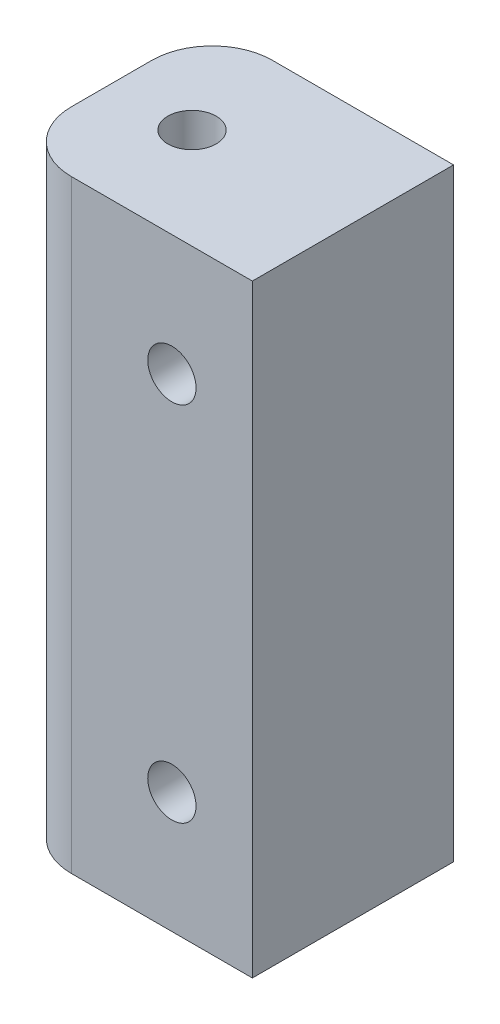
SolidWorks part; units mm, degrees
material "ABS"
ref_plane "Plan de face" through (0, 0, 0) normal (0, 0, 1) x (1, 0, 0)
ref_plane "Plan de dessus" through (0, 0, 0) normal (0, 1, 0) x (1, 0, 0)
ref_plane "Plan de droite" through (0, 0, 0) normal (1, 0, 0) x (0, 0, -1)
sketch "Esquisse1" plane through (0, 0, 0) normal (0, 1, 0) x (1, 0, 0)
  line L1 (-6, 10) -> (6, 10)
  line L2 (-6, 10) -> (-6, 0)
  line L3 (-6, 0) -> (6, 0)
  line L4 (6, 10) -> (6, 0)
  circle A0 centre (-2, 5) radius 1.2
  dimension "D3" = 2.4
  dimension "D4" = 4
  dimension "D5" = 5
  dimension "D1" = 12
  dimension "D2" = 10
extrude "Boss.-Extru.1" add sketch "Esquisse1" along normal mid plane 30
sketch "Esquisse2" plane through (0, 0, 0) normal (0, 0, 1) x (1, 0, 0)
  line L1 (-6, 0) -> (6, 0) construction
  line L2 (-6, 15) -> (-6, -15) construction
  line L3 (6, 15) -> (6, -15) construction
  circle A0 centre (2, 9) radius 1.2
  circle A1 centre (2, -9) radius 1.2
  dimension "D1" = 18
  dimension "D2" = 4
  dimension "D3" = 2.4
extrude "Enlèv. mat.-Extru.1" cut sketch "Esquisse2" against normal through all
fillet "Congé1" radius 3 2 edges at (-6, 0, -10) (-6, 0, 0)
